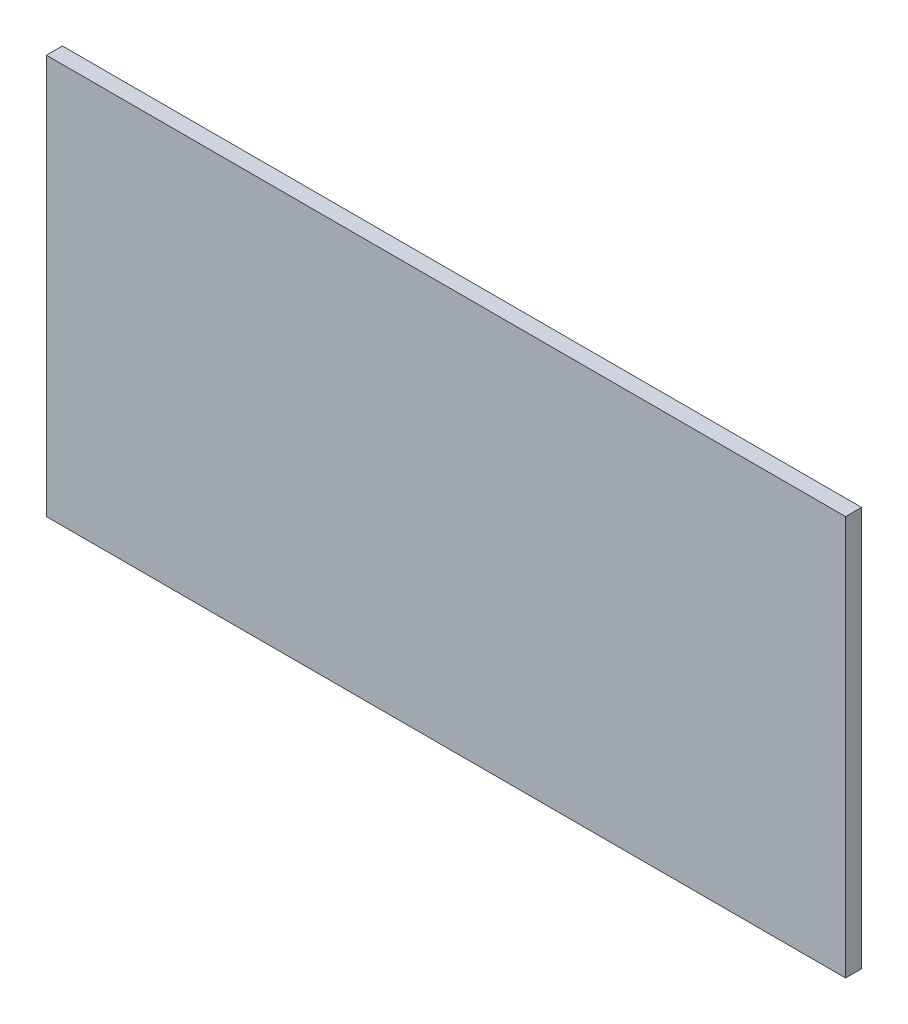
SolidWorks part; units mm, degrees
material "普通碳钢"
ref_plane "前视基准面" through (0, 0, 0) normal (0, 0, 1) x (1, 0, 0)
ref_plane "上视基准面" through (0, 0, 0) normal (0, 1, 0) x (1, 0, 0)
ref_plane "右视基准面" through (0, 0, 0) normal (1, 0, 0) x (0, 0, -1)
sketch "草图1" plane through (0, 0, 0) normal (0, 0, 1) x (1, 0, 0)
  line L1 (-400, -200) -> (400, -200)
  line L2 (-400, -200) -> (-400, 200)
  line L3 (-400, 200) -> (400, 200)
  line L4 (400, -200) -> (400, 200)
  line L5 (-400, -200) -> (400, 200) construction
  line L6 (-400, 200) -> (400, -200) construction
  point P0 (0, 0)
  dimension "D1" = 400
  dimension "D2" = 800
extrude "凸台-拉伸1" add sketch "草图1" along normal blind 16
